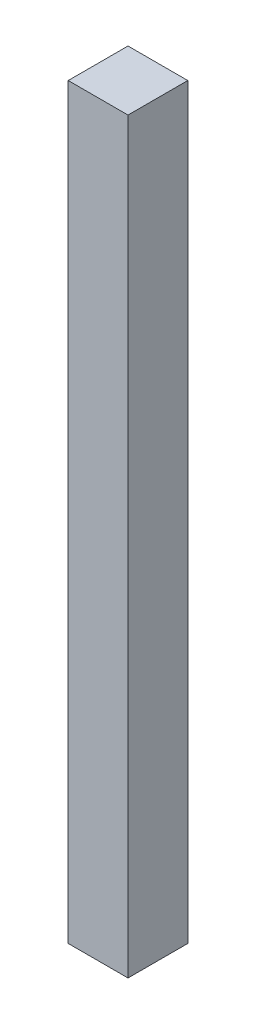
SolidWorks part; units mm, degrees
ref_plane "Front Plane" through (0, 0, 0) normal (0, 0, 1) x (1, 0, 0)
ref_plane "Top Plane" through (0, 0, 0) normal (0, 1, 0) x (1, 0, 0)
ref_plane "Right Plane" through (0, 0, 0) normal (1, 0, 0) x (0, 0, -1)
sketch "Sketch1" plane through (0, 0, 0) normal (0, 1, 0) x (1, 0, 0)
  line L1 (-10, -10) -> (10, -10)
  line L2 (-10, -10) -> (-10, 10)
  line L3 (-10, 10) -> (10, 10)
  line L4 (10, -10) -> (10, 10)
  line L5 (-10, -10) -> (10, 10) construction
  line L6 (-10, 10) -> (10, -10) construction
  point P0 (0, 0)
  dimension "D1" = 20
extrude "Boss-Extrude1" add sketch "Sketch1" along normal blind 250
sketch "Sketch2" plane through (0, 0, 0) normal (0, -1, 0) x (1, 0, 0)
  line L0 (0, 10) -> (0, -10) construction
  line L1 (-10, 10) -> (10, 10) construction
  line L2 (10, -10) -> (-10, -10) construction
  line L3 (10, 0) -> (-10, 0) construction
  line L4 (10, 10) -> (10, -10) construction
  line L5 (-10, -10) -> (-10, 10) construction
